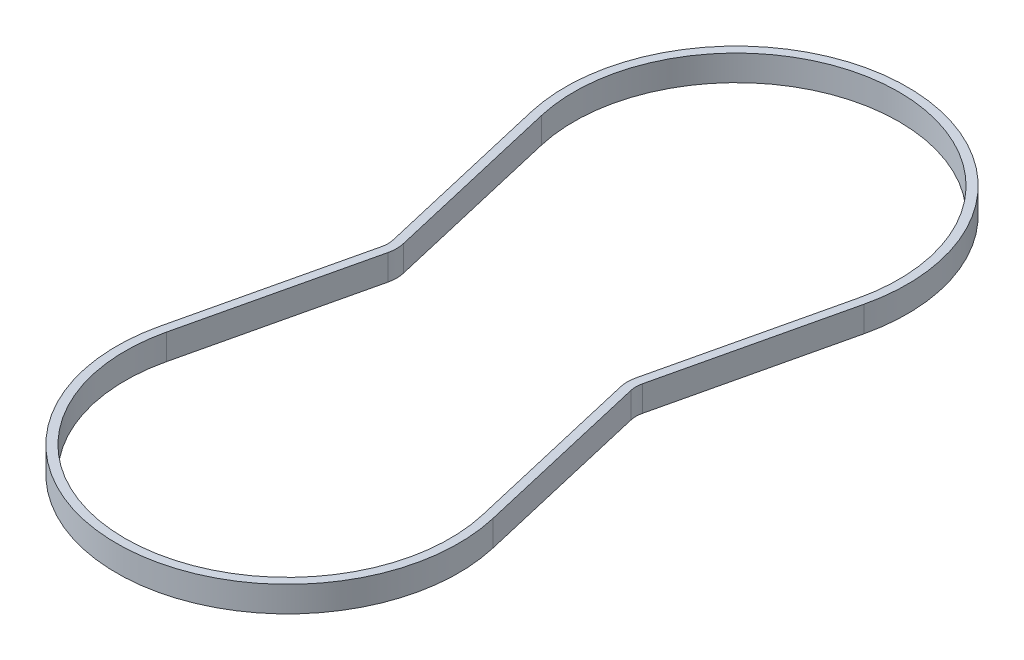
SolidWorks part; units mm, degrees
material "聚亚安酯(11671)"
ref_plane "前视基准面" through (0, 0, 0) normal (0, 0, 1) x (1, 0, 0)
ref_plane "上视基准面" through (0, 0, 0) normal (0, 1, 0) x (1, 0, 0)
ref_plane "右视基准面" through (0, 0, 0) normal (1, 0, 0) x (0, 0, -1)
sketch "草图1" plane through (0, 0, 0) normal (0, 1, 0) x (1, 0, 0)
  line L0 (0, -52.5) -> (0, 52.5) construction
  line L1 (-35, 0) -> (35, 0) construction
  line L2 (-38.9566, 43.4234) -> (-29.1565, 1.3615)
  line L3 (-38.9566, -43.4234) -> (-29.1565, -1.3615)
  line L4 (38.9566, 43.4234) -> (29.1565, 1.3615)
  line L5 (29.1565, -1.3615) -> (38.9566, -43.4234)
  arc A0 (-38.9566, -43.4234) -> (38.9566, -43.4234) centre (0, -52.5) ccw
  arc A1 (38.9566, 43.4234) -> (-38.9566, 43.4234) centre (0, 52.5) ccw
  arc A2 (-29.1565, -1.3615) -> (-29.1565, 1.3615) centre (-35, 0) ccw
  arc A4 (29.1565, 1.3615) -> (29.1565, -1.3615) centre (35, 0) ccw
  dimension "D1" = 80
  dimension "D2" = 105
  dimension "D3" = 6
  dimension "D4" = 70
extrude "拉伸-薄壁1" add sketch "草图1" along normal blind 6 thin thin type one direction reverse wall 2
